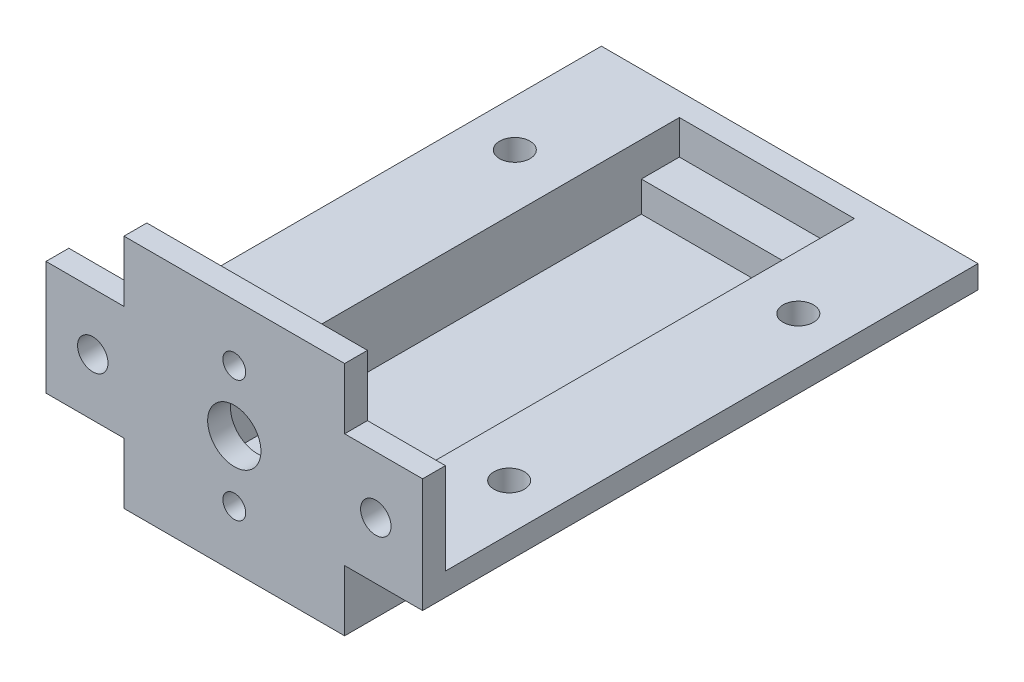
SolidWorks part; units mm, degrees
ref_plane "Alzado" through (0, 0, 0) normal (0, 0, 1) x (1, 0, 0)
ref_plane "Planta" through (0, 0, 0) normal (0, 1, 0) x (1, 0, 0)
ref_plane "Vista lateral" through (0, 0, 0) normal (1, 0, 0) x (0, 0, -1)
sketch "Croquis4" plane through (0, 0, 0) normal (0, 0, 1) x (1, 0, 0)
  line L1 (14.5, 16) -> (-14.5, 16)
  line L2 (-14.5, 16) -> (-14.5, 8)
  line L3 (-14.5, 8) -> (-24.75, 8)
  line L4 (-24.75, 8) -> (-24.75, -7)
  line L5 (-24.75, -7) -> (-14.5, -7)
  line L6 (-14.5, -7) -> (-14.5, -15)
  line L7 (-14.5, -15) -> (14.5, -15)
  line L8 (14.5, -7) -> (14.5, -15)
  line L9 (24.75, -7) -> (14.5, -7)
  line L10 (24.75, 8) -> (24.75, -7)
  line L11 (14.5, 8) -> (24.75, 8)
  line L12 (14.5, 16) -> (14.5, 8)
  point P4 (0, 0)
  dimension "D1" = 29
  dimension "D2" = 10.25
  dimension "D3" = 8
  dimension "D4" = 15
extrude "Saliente-Extruir2" add sketch "Croquis4" along normal blind 3
sketch "Croquis5" plane through (0, 0, 0) normal (0, 0, -1) x (-1, 0, 0)
  line L26 (-24.75, -4) -> (-24.75, -7)
  line L27 (-24.75, -7) -> (-24.75, 8) construction
  line L28 (-24.75, -7) -> (-14.5, -7)
  line L29 (14.5, -7) -> (24.75, -7)
  line L31 (24.75, -7) -> (24.75, -4)
  line L32 (-14.5, -7) -> (-24.75, -7) construction
  line L33 (24.75, 8) -> (24.75, -7) construction
  line L34 (24.75, -4) -> (-24.75, -4)
  line L38 (-14.5, -7) -> (-14.5, -15)
  line L39 (-14.5, -15) -> (14.5, -15)
  line L40 (14.5, -7) -> (14.5, -15) construction
  line L41 (14.5, -15) -> (14.5, -7)
  dimension "D1" = 3
extrude "Saliente-Extruir3" add sketch "Croquis5" along normal blind 70
sketch "croquis hueco motor" plane through (0, -4, 0) normal (0, 1, 0) x (1, 0, 0)
  line L0 (14.5, 0) -> (-14.5, 0) construction
  line L6 (-11.5, 0) -> (11.5, 0)
  line L8 (-11.5, 0) -> (-11.5, 67)
  line L12 (-11.5, 67) -> (11.5, 67)
  line L14 (11.5, 0) -> (11.5, 67)
  line L17 (-24.75, 70) -> (24.75, 70) construction
  line L18 (-11.5, 54.716) -> (-24.75, 54.716) construction
  line L19 (-24.75, 70) -> (-24.75, 0) construction
  line L20 (11.5, 55.3959) -> (24.75, 55.3959) construction
  line L21 (24.75, 70) -> (24.75, 0) construction
  dimension "D1" = 23
  dimension "D2" = 3
extrude "hueco motor" cut sketch "croquis hueco motor" against normal blind 8.5
sketch "Croquis10" plane through (0, 0, 3) normal (0, 0, 1) x (1, 0, 0)
  line L0 (-14.5, 16) -> (14.5, -15) construction
  line L1 (14.5, -15) -> (14.5, 16) construction
  line L2 (14.5, 16) -> (-14.5, -15) construction
  line L3 (-24.75, 8) -> (-24.75, -7) construction
  line L4 (-24.75, 0.5) -> (24.75, 0.5) construction
  line L5 (-14.5, 8) -> (-24.75, 8) construction
  line L6 (0, 0.5) -> (0, 16) construction
  line L7 (24.75, -7) -> (24.75, 8) construction
  line L9 (14.5, 16) -> (-14.5, 16) construction
  circle A0 centre (0, 0.5) radius 3.5
  circle A1 centre (-18.6, 0.5) radius 2
  circle A2 centre (18.6, 0.5) radius 2
  circle A3 centre (0, 8.5) radius 1.5
  circle A4 centre (0, -7.5) radius 1.5
  dimension "D1" = 6.15
  dimension "D2" = 4
  dimension "D4" = 7
  dimension "D6" = 3
  dimension "D3" = 7.5
  dimension "D5" = 8
extrude "tornillo y motor" cut sketch "Croquis10" against normal blind 5
sketch "Croquis12" plane through (0, -12.5, 0) normal (0, 1, 0) x (1, 0, 0)
  line L6 (11.5, 0) -> (11.5, 67) construction
  line L7 (-11.5, 67) -> (11.5, 67)
  line L8 (-11.5, 67) -> (-11.5, 62)
  line L9 (-11.5, 62) -> (11.5, 62)
  line L10 (11.5, 67) -> (11.5, 62)
  dimension "D1" = 5
extrude "Saliente-Extruir5" add sketch "Croquis12" along normal blind 4
sketch "Croquis16" plane through (0, -4, 0) normal (0, 1, 0) x (1, 0, 0)
  line L0 (-18.63, 52.5) -> (18.63, 52.5) construction
  line L1 (18.63, 52.5) -> (18.63, 14.5) construction
  line L2 (-18.63, 52.5) -> (-24.75, 52.5) construction
  line L3 (24.75, 70) -> (24.75, 0) construction
  line L7 (-18.63, 14.5) -> (-24.7537, 14.5) construction
  line L10 (18.63, 14.5) -> (24.7537, 14.5) construction
  line L12 (18.63, 52.5) -> (24.7446, 52.1673) construction
  line L13 (-24.75, 70) -> (-24.75, 0) construction
  circle A0 centre (-18.63, 52.5) radius 2
  circle A1 centre (-18.63, 14.5) radius 2
  circle A2 centre (18.63, 14.5) radius 2
  circle A3 centre (18.63, 52.5) radius 2
  dimension "D1" = 38
  dimension "D2" = 38
  dimension "D3" = 6.12
  dimension "D4" = 6.12
extrude "Cortar-Extruir4" cut sketch "Croquis16" against normal through all
